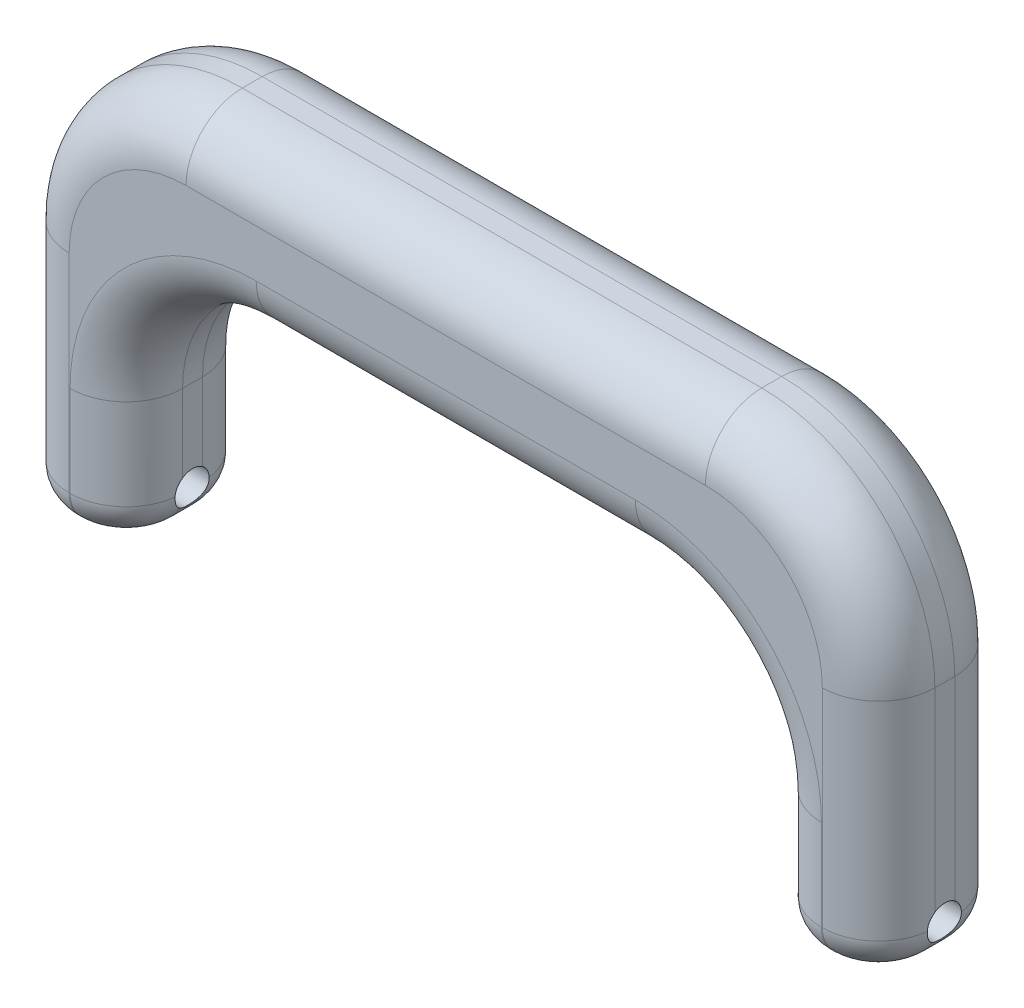
SolidWorks part; units mm, degrees
ref_plane "Front Plane" through (0, 0, 0) normal (0, 0, 1) x (1, 0, 0)
ref_plane "Top Plane" through (0, 0, 0) normal (0, 1, 0) x (1, 0, 0)
ref_plane "Right Plane" through (0, 0, 0) normal (1, 0, 0) x (0, 0, -1)
sketch "Sketch1" plane through (0, 0, 0) normal (0, 0, 1) x (1, 0, 0)
  line L0 (0, -1094.4215) -> (0, 53626.6557) construction
  line L1 (-46.863, 0) -> (-46.863, 18.415)
  line L2 (-46.863, 0) -> (-63.5, 0)
  line L3 (-63.5, 0) -> (-63.5, 35.56)
  line L4 (-1139.1946, 37.465) -> (53581.8826, 37.465) construction
  line L5 (-1139.1946, 60.96) -> (53581.8826, 60.96) construction
  line L6 (63.5, 0) -> (63.5, 35.56)
  line L7 (46.863, 0) -> (63.5, 0)
  line L8 (46.863, 0) -> (46.863, 18.415)
  line L9 (-27.813, 37.465) -> (27.813, 37.465)
  line L11 (-38.1, 60.96) -> (38.1, 60.96)
  arc A0 (-46.863, 18.415) -> (-27.813, 37.465) centre (-27.813, 18.415) cw
  arc A1 (-63.5, 35.56) -> (-38.1, 60.96) centre (-38.1, 35.56) cw
  arc A2 (63.5, 35.56) -> (38.1, 60.96) centre (38.1, 35.56) ccw
  arc A3 (46.863, 18.415) -> (27.813, 37.465) centre (27.813, 18.415) ccw
  dimension "D4" = 19.05
  dimension "D5" = 25.4
  dimension "D1" = 16.637
  dimension "D2" = 60.96
  dimension "D3" = 37.465
  dimension "D6" = 127
extrude "Boss-Extrude1" add sketch "Sketch1" along normal mid plane 19.431 contours L11 A2 L6 L7 L8 A3 L9 A0 L1 L2 L3 A1
fillet "Fillet2" radius 8.255 20 edges at (-46.863, 9.2075, -9.7155) (-41.2834, 31.8854, -9.7155) (46.863, 9.2075, -9.7155) (41.2834, 31.8854, -9.7155) (-63.5, 17.78, -9.7155) (-56.0605, 53.5205, -9.7155) (63.5, 17.78, -9.7155) (56.0605, 53.5205, -9.7155) (-63.5, 17.78, 9.7155) (-56.0605, 53.5205, 9.7155) (63.5, 17.78, 9.7155) (56.0605, 53.5205, 9.7155) (0, 37.465, -9.7155) (0, 60.96, -9.7155) (0, 60.96, 9.7155) (-46.863, 9.2075, 9.7155) (-41.2834, 31.8854, 9.7155) (46.863, 9.2075, 9.7155) (41.2834, 31.8854, 9.7155) (0, 37.465, 9.7155)
fillet "Fillet4" radius 5.08 16 edges at (-49.2808, 0, -7.2977) (-55.1815, 0, -9.7155) (-55.1815, 0, 9.7155) (-49.2808, 0, 7.2977) (-46.863, 0, 0) (55.1815, 0, -9.7155) (49.2808, 0, -7.2977) (46.863, 0, 0) (49.2808, 0, 7.2977) (55.1815, 0, 9.7155) (61.0822, 0, 7.2977) (63.5, 0, 0) (61.0822, 0, -7.2977) (-61.0822, 0, -7.2977) (-63.5, 0, 0) (-61.0822, 0, 7.2977)
sketch "Croquis2" plane through (0, 0, 0) normal (1, 0, 0) x (0, 0, -1)
  line L0 (1.4605, 0) -> (4.6355, 0) construction
  circle A0 centre (0, 5) radius 2.5
  dimension "D1" = 5
  dimension "D2" = 5
extrude "Cortar-Extruir2" cut sketch "Croquis2" against normal mid plane 155.448
